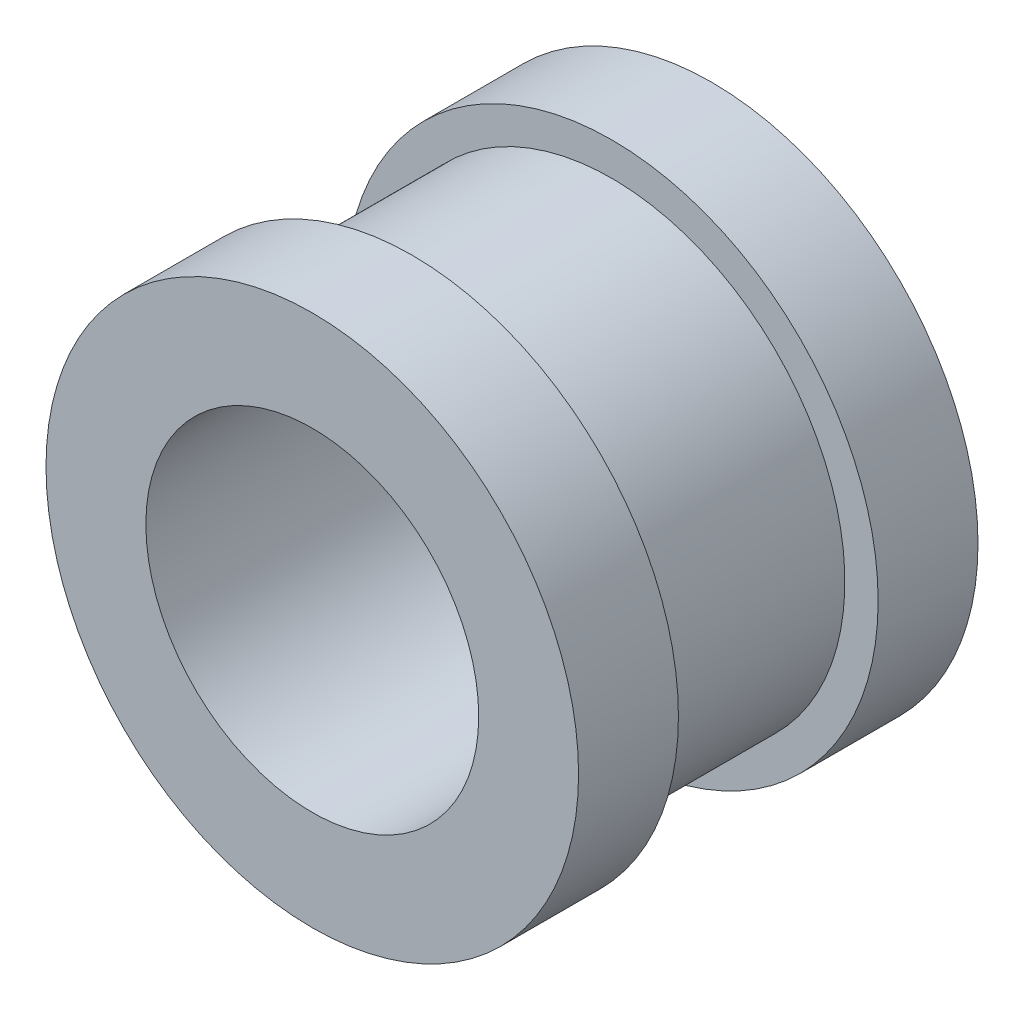
SolidWorks part; units mm, degrees
material "Alumina"
ref_plane "Front Plane" through (0, 0, 0) normal (0, 0, 1) x (1, 0, 0)
ref_plane "Top Plane" through (0, 0, 0) normal (0, 1, 0) x (1, 0, 0)
ref_plane "Right Plane" through (0, 0, 0) normal (1, 0, 0) x (0, 0, -1)
sketch "Sketch1" plane through (0, 0, 0) normal (0, 0, 1) x (1, 0, 0)
  circle A0 centre (0, 0) radius 8
  circle A1 centre (0, 0) radius 5
  dimension "D1" = 16
  dimension "D2" = 10
extrude "Boss-Extrude1" add sketch "Sketch1" along normal blind 12
sketch "Sketch2" plane through (0, 0, 0) normal (0, 1, 0) x (1, 0, 0)
  line L0 (-8, 0) -> (-8, -12) construction
  line L1 (-8, -3) -> (-7, -3)
  line L2 (-8, -3) -> (-8, -9)
  line L3 (-8, -9) -> (-7, -9)
  line L4 (-7, -3) -> (-7, -9)
  line L5 (8, 0) -> (-8, 0) construction
  line L6 (-8, -12) -> (8, -12) construction
  dimension "D1" = 3
  dimension "D2" = 3
  dimension "D3" = 1
sketch "Sketch3" plane through (0, 0, 0) normal (0, 1, 0) x (1, 0, 0)
  line L0 (0, 2.7302) -> (0, -12) construction
  line L1 (-8, -12) -> (8, -12) construction
revolve "Cut-Revolve1" cut sketch "Sketch2" angle 360 about L0
